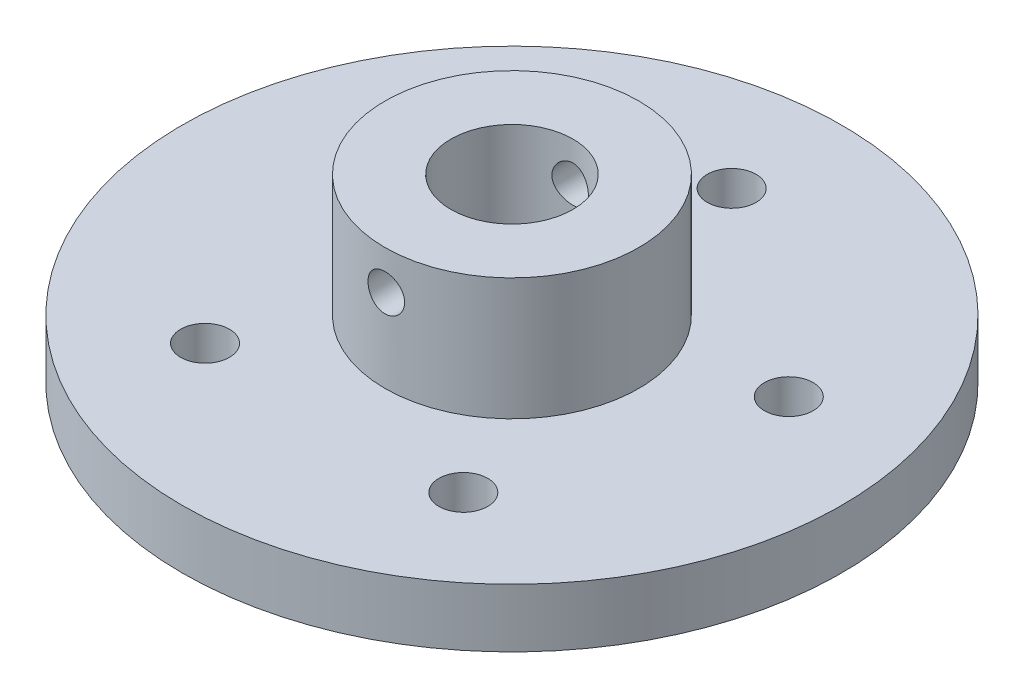
SolidWorks part; units mm, degrees
material "Delrin 2700 NC010, Low Viscosity Acetal Copolymer (SS)"
ref_plane "Front Plane" through (0, 0, 0) normal (0, 0, 1) x (1, 0, 0)
ref_plane "Top Plane" through (0, 0, 0) normal (0, 1, 0) x (1, 0, 0)
ref_plane "Right Plane" through (0, 0, 0) normal (1, 0, 0) x (0, 0, -1)
sketch "Sketch1" plane through (0, 0, 0) normal (0, 0, 1) x (1, 0, 0)
  line L0 (0, 7.8095) -> (0, 0) construction
  line L1 (0, 0) -> (15.875, 0) construction
  line L3 (15.875, 0) -> (85.725, 0)
  line L4 (15.875, 0) -> (15.875, 15.24)
  line L5 (15.875, 15.24) -> (85.725, 15.24)
  line L6 (85.725, 0) -> (85.725, 15.24)
  line L7 (15.875, 15.24) -> (33.02, 15.24)
  line L8 (15.875, 15.24) -> (15.875, 46.99)
  line L9 (15.875, 46.99) -> (33.02, 46.99)
  line L10 (33.02, 15.24) -> (33.02, 46.99)
  dimension "D1" = 15.875
  dimension "D2" = 15.24
  dimension "D3" = 33.02
  dimension "D4" = 31.75
  dimension "5.5" = 69.85
revolve "Revolve1" add sketch "Sketch1" angle 360 about L0
sketch "Sketch2" plane through (0, 15.24, 0) normal (0, 1, 0) x (1, 0, 0)
  line L0 (0, 57.15) -> (54.3529, 17.6603) construction
  line L1 (54.3529, 17.6603) -> (33.5919, -46.2353) construction
  line L2 (33.5919, -46.2353) -> (-33.5919, -46.2353) construction
  line L3 (-33.5919, -46.2353) -> (-54.3529, 17.6603) construction
  line L4 (-54.3529, 17.6603) -> (0, 57.15) construction
  circle A0 centre (0, 0) radius 57.15 construction
  point P3 (-54.3529, 17.6603)
  point P4 (0, 57.15)
  point P5 (54.3529, 17.6603)
  point P6 (-33.5919, -46.2353)
  point P7 (33.5919, -46.2353)
  dimension "D1" = 114.3
hole_wizard "1/2 (0.5) Diameter Hole1" positions "Sketch3" profile "Sketch4" hole size "1/2" standard "ANSI Inch" end condition through all
sketch "Sketch3" plane through (0, 15.24, 0) normal (0, 1, 0) x (1, 0, 0)
  point P0 (-54.3529, 17.6603)
  point P3 (0, 57.15)
  point P6 (54.3529, 17.6603)
  point P9 (33.5919, -46.2353)
  point P12 (-33.5919, -46.2353)
sketch "Sketch4" plane through (-54.3529, 15.24, -17.6603) normal (1, 0, 0) x (0, 0, 1)
  line L0 (0, 0) -> (0, 15.24)
  line L1 (0, 15.24) -> (6.35, 15.24)
  line L2 (6.35, 15.24) -> (6.35, 0)
  line L5 (6.35, 0) -> (0, 0)
  line L11 (0, -6.35) -> (0, 107.95) construction
  dimension "Thru Hole Dia." = 12.7
  dimension "Thru Hole Depth" = 15.24
sketch "Sketch10" plane through (0, 0, 0) normal (0, 0, 1) x (1, 0, 0)
  line L0 (15.875, 46.99) -> (-15.875, 46.99) construction
  circle A0 centre (0, 36.83) radius 4.7625
  dimension "D2" = 9.525
  dimension "D1" = 10.16
extrude "Cut-Extrude1" cut sketch "Sketch10" against normal through all both and the other way through all
